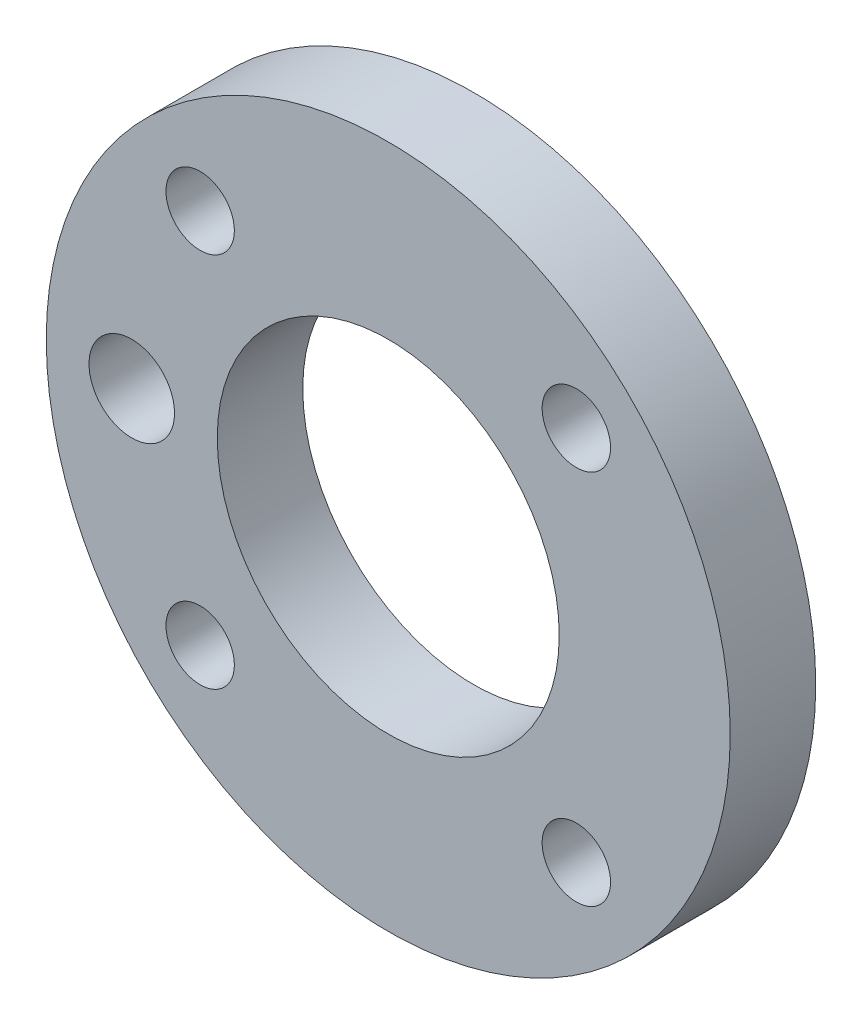
SolidWorks part; units mm, degrees
ref_plane "Front Plane" through (0, 0, 0) normal (0, 0, 1) x (1, 0, 0)
ref_plane "Top Plane" through (0, 0, 0) normal (0, 1, 0) x (1, 0, 0)
ref_plane "Right Plane" through (0, 0, 0) normal (1, 0, 0) x (0, 0, -1)
sketch "Sketch1" plane through (0, 0, 0) normal (0, 0, 1) x (1, 0, 0)
  line L1 (-11, 11) -> (11, 11) construction
  line L2 (-11, 11) -> (-11, -11) construction
  line L3 (-11, -11) -> (11, -11) construction
  line L4 (11, 11) -> (11, -11) construction
  line L5 (-11, 11) -> (11, -11) construction
  line L6 (-11, -11) -> (11, 11) construction
  circle A0 centre (0, 0) radius 20
  circle A1 centre (0, 0) radius 10
  circle A2 centre (-11, 11) radius 2
  circle A3 centre (11, 11) radius 2
  circle A4 centre (11, -11) radius 2
  circle A5 centre (-11, -11) radius 2
  circle A6 centre (-15, 0) radius 2.5
  dimension "D1" = 40
  dimension "D2" = 20
  dimension "D5" = 4
  dimension "D8" = 5
  dimension "D3" = 22
  dimension "D4" = 22
  dimension "D9" = 15
  dimension "D6" = 2
  dimension "D7" = 2
extrude "Boss-Extrude1" add sketch "Sketch1" along normal blind 5
